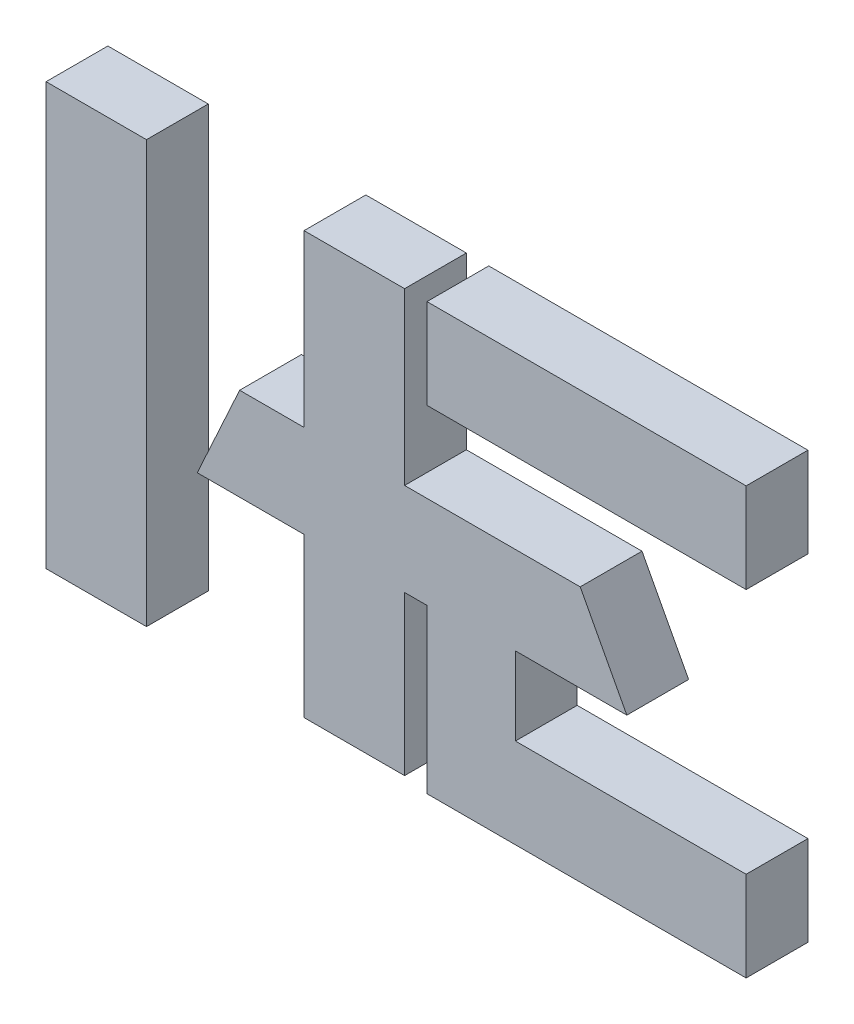
SolidWorks part; units mm, degrees
ref_plane "Front Plane" through (0, 0, 0) normal (0, 0, 1) x (1, 0, 0)
ref_plane "Top Plane" through (0, 0, 0) normal (0, 1, 0) x (1, 0, 0)
ref_plane "Right Plane" through (0, 0, 0) normal (1, 0, 0) x (0, 0, -1)
sketch "Sketch1" plane through (0, 0, 0) normal (0, 0, 1) x (1, 0, 0)
  line L0 (-3.8951, 1.0348) -> (-4.9505, -1.272)
  line L1 (-8.7145, 5.2778) -> (-6.2145, 5.2778)
  line L2 (-8.7145, 5.2778) -> (-8.7145, -5.2222)
  line L3 (-8.7145, -5.2222) -> (-6.2145, -5.2222)
  line L4 (-6.2145, 5.2778) -> (-6.2145, -5.2222)
  line L5 (8.7145, 5.2778) -> (0.7689, 5.2778)
  line L6 (8.7145, 5.2778) -> (8.7145, 3.0408)
  line L7 (8.7145, 3.0408) -> (0.7689, 3.0408)
  line L8 (0.7689, 5.2778) -> (0.7689, 3.0408)
  line L9 (8.7145, -3.0963) -> (2.9702, -3.0963)
  line L10 (8.7145, -3.0963) -> (8.7145, -5.3334)
  line L11 (8.7145, -5.3334) -> (0.7689, -5.3334)
  line L13 (0.7689, -5.3334) -> (0.7689, -1.272)
  line L14 (0.7689, 1.0348) -> (2.9702, 1.0348)
  line L15 (2.9702, -3.0963) -> (2.9702, -1.1514)
  line L16 (2.9702, 1.0348) -> (4.5834, 1.0348)
  line L17 (2.9702, -1.1514) -> (4.5834, -1.1514)
  line L18 (0.7689, -1.272) -> (0.2111, -1.272)
  line L19 (0.7689, 1.0348) -> (0.2111, 1.0348)
  line L20 (0.2111, 5.2778) -> (-2.2917, 5.2778)
  line L21 (0.2111, 5.2778) -> (0.2111, 1.0348)
  line L22 (0.2111, -5.2222) -> (-2.2917, -5.2222)
  line L23 (-2.2917, 5.2778) -> (-2.2917, 1.0348)
  line L24 (-4.9505, -1.272) -> (-3.8553, -1.272)
  line L25 (4.5834, -1.1514) -> (5.7443, -1.1514)
  line L26 (5.7443, -1.1514) -> (4.5834, 1.0348)
  line L27 (-2.2917, 1.0348) -> (-3.8951, 1.0348)
  line L28 (0.2111, -1.272) -> (0.2111, -5.2222)
  line L29 (-2.2917, -1.272) -> (-2.2917, -5.2222)
  line L30 (-2.2917, -1.272) -> (-3.8553, -1.272)
  line L31 (8.7145, 3.0408) -> (8.7145, -3.0963) construction
  line L32 (8.7145, -0.0278) -> (-8.7145, 0.0278) construction
  line L33 (0, 5.2222) -> (0, -5.2222) construction
  point P35 (0, 0)
  dimension "D1" = 2.5
  dimension "D2" = 10.5
  dimension "D3" = 10.5
  dimension "D4" = 4.243
  dimension "D5" = 2.3068
  dimension "D6" = 0.5578
  dimension "D7" = 2.2012
  dimension "D8" = 1.6132
  dimension "D9" = 2.1862
  dimension "D10" = 1.1609
  dimension "D11" = 1.6132
  dimension "D12" = 1.9449
  dimension "D13" = 5.7443
  dimension "D14" = 7.9456
  dimension "D15" = 0.5578
  dimension "D16" = 2.5028
  dimension "D17" = 7.9456
  dimension "D18" = 2.006
  dimension "D19" = 3.9228
  dimension "D20" = 0.5578
  dimension "D21" = 1.0554
  dimension "D22" = 1.0953
  dimension "D23" = 1.264
extrude "Boss-Extrude1" add sketch "Sketch1" along normal blind 2
scale "Scale2" bodies to scale 101 103 102 scale about origin uniform scaling yes scale factor 1.3
sketch "Sketch2" plane through (0, 0, 2.6) normal (0, 0, 1) x (1, 0, 0)
  line L1 (-15.0233, 8.784) -> (13.9733, 8.784)
  line L2 (-15.0233, 8.784) -> (-15.0233, -8.3393)
  line L3 (-15.0233, -8.3393) -> (13.9733, -8.3393)
  line L4 (13.9733, 8.784) -> (13.9733, -8.3393)
extrude "Cut-Extrude1" cut sketch "Sketch2" against normal blind 0.6
